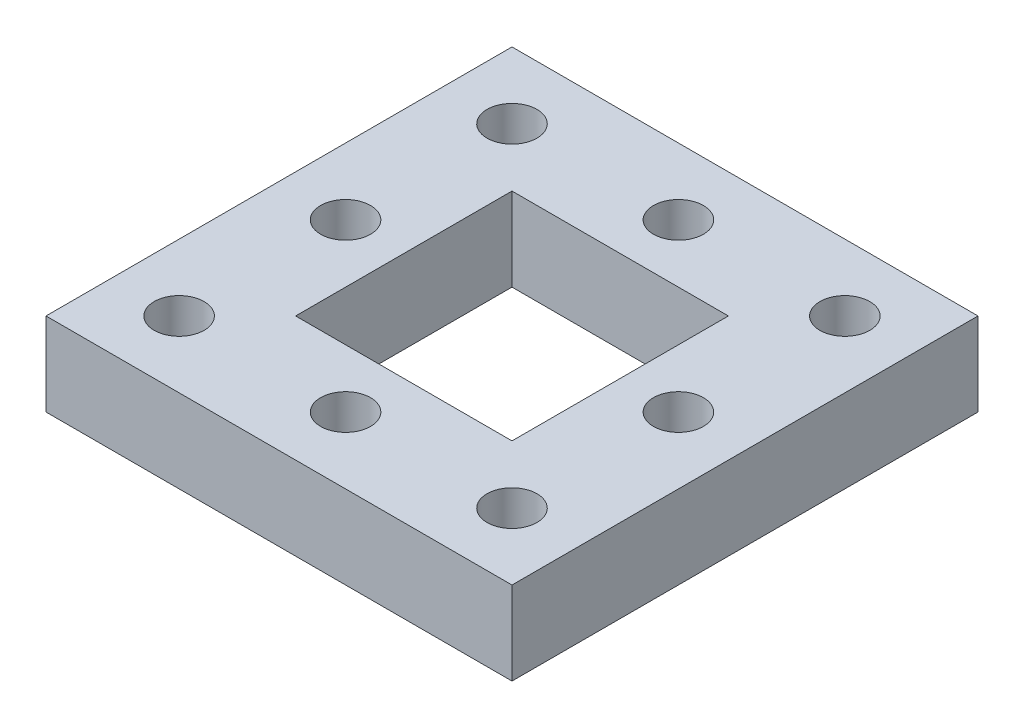
SolidWorks part; units mm, degrees
ref_plane "Спереди" through (0, 0, 0) normal (0, 0, 1) x (1, 0, 0)
ref_plane "Сверху" through (0, 0, 0) normal (0, 1, 0) x (1, 0, 0)
ref_plane "Справа" through (0, 0, 0) normal (1, 0, 0) x (0, 0, -1)
sketch "Эскиз1" plane through (0, 0, 0) normal (0, 1, 0) x (1, 0, 0)
  line L0 (0, 0) -> (28, 0)
  line L1 (0, 0) -> (0, 28)
  line L2 (28, 0) -> (28, 28)
  line L3 (0, 28) -> (28, 28)
  line L4 (7.5, 20.5) -> (20.5, 20.5)
  line L5 (7.5, 20.5) -> (7.5, 7.5)
  line L6 (20.5, 20.5) -> (20.5, 7.5)
  line L7 (7.5, 7.5) -> (20.5, 7.5)
  line L8 (14, 28) -> (14, 0) construction
  line L9 (28, 14) -> (0, 14) construction
  point P13 (14, 20.5)
  point P14 (20.5, 14)
  dimension "D1" = 13
  dimension "D2" = 28
extrude "Бобышка-Вытянуть1" add sketch "Эскиз1" along normal blind 5
sketch "Эскиз2" plane through (0, 5, 0) normal (0, 1, 0) x (1, 0, 0)
  line L0 (14, 28) -> (14, 0) construction
  line L1 (28, 28) -> (0, 28) construction
  line L2 (0, 0) -> (28, 0) construction
  line L3 (28, 14) -> (0, 14) construction
  line L4 (28, 0) -> (28, 28) construction
  line L5 (0, 28) -> (0, 0) construction
sketch "Эскиз3" plane through (0, 5, 0) normal (0, 1, 0) x (1, 0, 0)
  line L0 (28, 0) -> (28, 28) construction
  line L1 (28, 28) -> (0, 28) construction
  circle A0 centre (24, 24) radius 1.5
  dimension "D1" = 4
  dimension "D2" = 4
  dimension "D3" = 3
extrude "Вырез-Вытянуть1" cut sketch "Эскиз3" against normal through all
sketch "Эскиз4" plane through (0, 5, 0) normal (0, 1, 0) x (1, 0, 0)
  line L0 (22.5, 24) -> (25.5, 24) construction
  circle A0 centre (24, 24) radius 1.5 construction
ref_plane "Плоскость1" through (0, 0, -24) normal (0, 0, 1) x (1, 0, 0)
sketch "Эскиз5" plane through (0, 0, -24) normal (0, 0, 1) x (1, 0, 0)
  line L0 (25.5, 5) -> (28, 5)
  line L1 (25.5, 5) -> (27, 9)
  line L2 (27, 9) -> (28, 9)
  line L3 (28, 9) -> (28, 5)
  dimension "D1" = 4
  dimension "D2" = 1
sketch "Эскиз6" plane through (0, 5, 0) normal (0, 1, 0) x (1, 0, 0)
  line L0 (24, 24) -> (4, 24) construction
  line L3 (24, 24) -> (24, 4) construction
  line L4 (1.75, 1.75) -> (26.25, 1.75)
  line L5 (26.25, 1.75) -> (26.25, 26.25)
  line L6 (26.25, 26.25) -> (1.75, 26.25)
  line L7 (1.75, 26.25) -> (1.75, 1.75)
  line L8 (1.75, 1.75) -> (26.25, 1.75) construction
  line L9 (26.25, 1.75) -> (26.25, 26.25) construction
  line L10 (26.25, 26.25) -> (1.75, 26.25) construction
  line L11 (1.75, 26.25) -> (1.75, 1.75) construction
  line L12 (4, 24) -> (4, 4) construction
  line L13 (24, 4) -> (4, 4) construction
  line L14 (22.5, 24) -> (25.5, 24) construction
  line L15 (-15.4, 24) -> (15.4, 24) construction
  line L16 (28, 14) -> (0, 14) construction
  line L17 (14, 28) -> (14, 0) construction
  circle A0 centre (4, 24) radius 1.5
  circle A1 centre (4, 4) radius 1.5
  circle A2 centre (24, 4) radius 1.5
  circle A3 centre (24, 14) radius 1.5
  circle A4 centre (14, 24) radius 1.5
  circle A5 centre (4, 14) radius 1.5
  circle A6 centre (14, 4) radius 1.5
  point P10 (24, 14)
  point P15 (14, 24)
  dimension "D2" = 3
  dimension "D1" = 0
extrude "Вырез-Вытянуть2" cut sketch "Эскиз6" against normal through all
